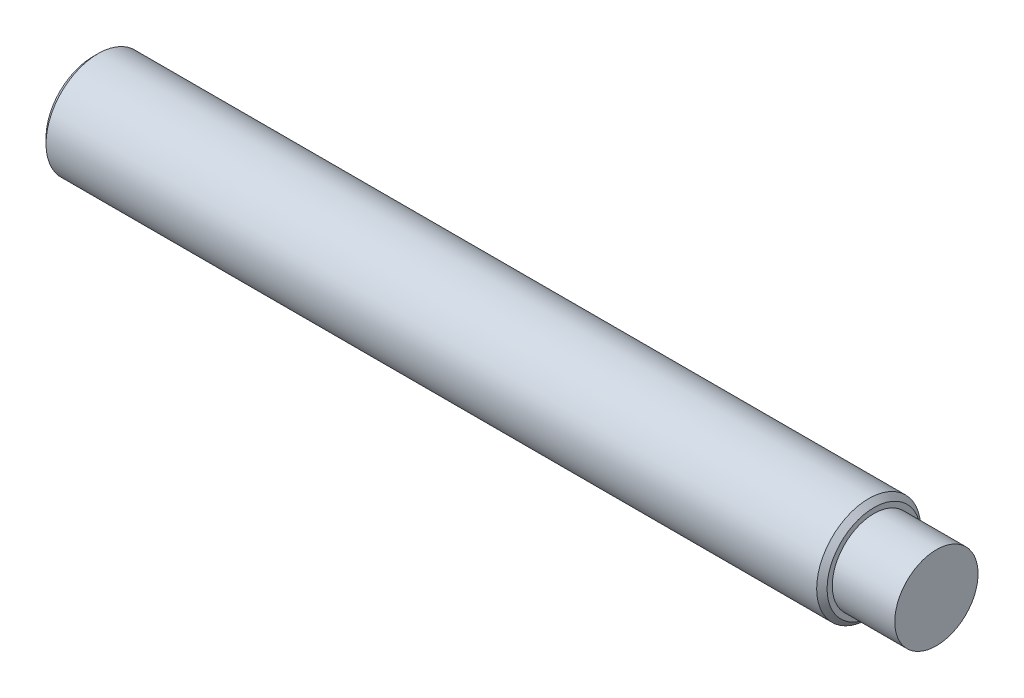
SolidWorks part; units mm, degrees
ref_plane "Front Plane" through (0, 0, 0) normal (0, 0, 1) x (1, 0, 0)
ref_plane "Top Plane" through (0, 0, 0) normal (0, 1, 0) x (1, 0, 0)
ref_plane "Right Plane" through (0, 0, 0) normal (1, 0, 0) x (0, 0, -1)
sketch "Sketch1" plane through (0, 0, 0) normal (0, 0, 1) x (1, 0, 0)
  line L0 (0, 0) -> (0, 5)
  line L1 (0, 5) -> (75, 5)
  line L2 (75, 5) -> (75, 4)
  line L3 (75, 4) -> (81, 4)
  line L4 (81, 4) -> (81, 0)
  line L5 (81, 0) -> (0, 0)
  line L6 (-21.6251, 0) -> (57.019, 0) construction
  dimension "D1" = 75
  dimension "D2" = 6
  dimension "D3" = 10
  dimension "D4" = 8
revolve "Revolve1" add sketch "Sketch1" angle 360 about L6
chamfer "Chamfer1" distance 0.5 angle 45 2 edges at (75, 0, 5) (0, 0, 5)
sketch "Sketch6" plane through (0, 0, 0) normal (-1, 0, 0) x (0, 0, 1)
  circle A0 centre (0, 0) radius 3
  dimension "D1" = 6
extrude "Cut-Extrude1" cut sketch "Sketch6" against normal blind 10
